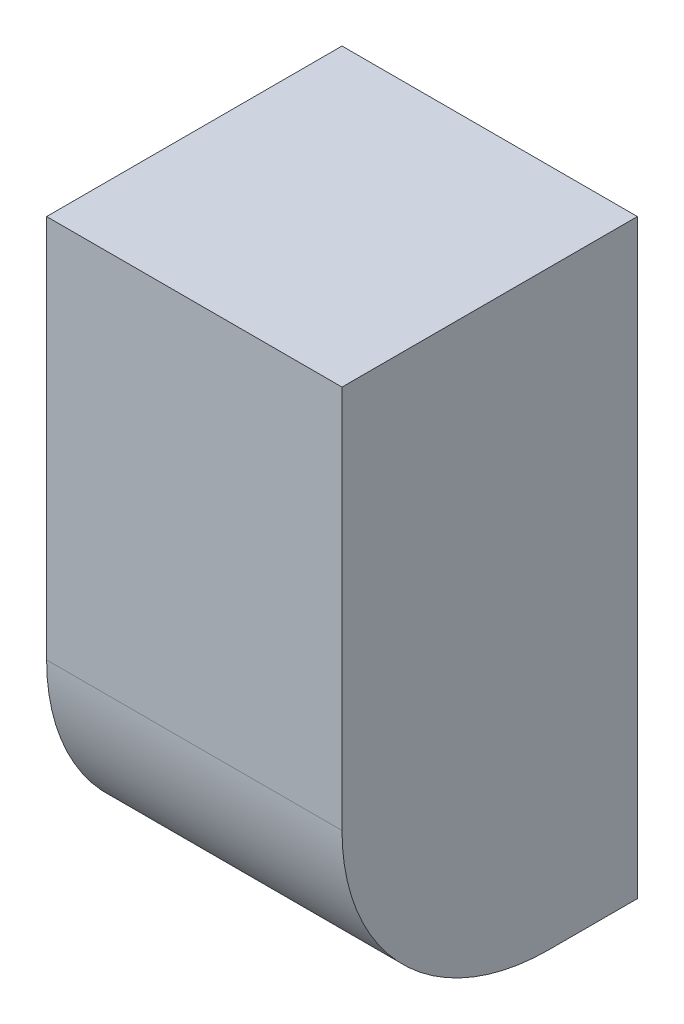
SolidWorks part; units mm, degrees
ref_plane "前视基准面" through (0, 0, 0) normal (0, 0, 1) x (1, 0, 0)
ref_plane "上视基准面" through (0, 0, 0) normal (0, 1, 0) x (1, 0, 0)
ref_plane "右视基准面" through (0, 0, 0) normal (1, 0, 0) x (0, 0, -1)
sketch "草图1" plane through (0, 0, 0) normal (0, 0, 1) x (1, 0, 0)
  line L1 (-40, -40) -> (-30, -40)
  line L2 (-40, -40) -> (-40, -20)
  line L3 (-40, -20) -> (-30, -20)
  line L4 (-30, -40) -> (-30, -20)
  dimension "D1" = 10
  dimension "D2" = 20
extrude "凸台-拉伸1" add sketch "草图1" along normal blind 10
fillet "圆角1" radius 7 1 edges at (-35, -40, 10)
